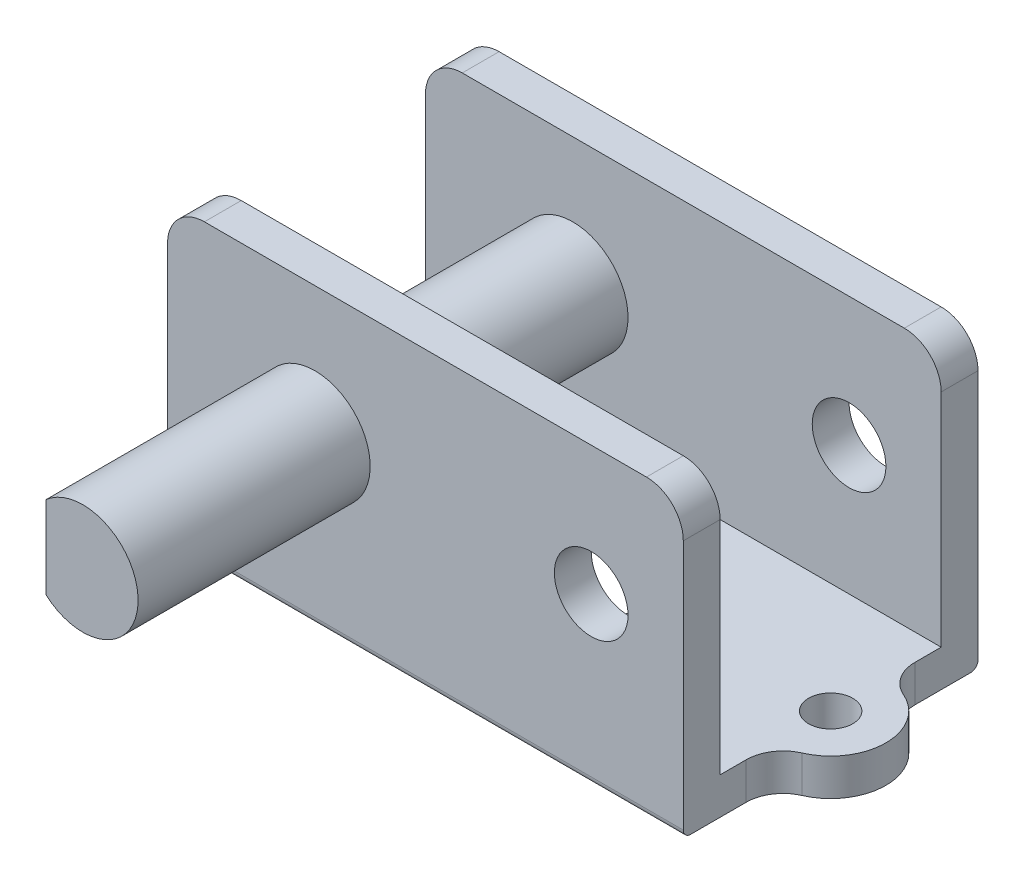
SolidWorks part; units mm, degrees
ref_plane "Спереди" through (0, 0, 0) normal (0, 0, 1) x (1, 0, 0)
ref_plane "Сверху" through (0, 0, 0) normal (0, 1, 0) x (1, 0, 0)
ref_plane "Справа" through (0, 0, 0) normal (1, 0, 0) x (0, 0, -1)
sketch "Sketch1" plane through (0, 0, 0) normal (0, 0, 1) x (1, 0, 0)
  line L0 (0, 0) -> (-7, 0)
  line L1 (-7, 0) -> (-7, 8)
  line L2 (-7, 8) -> (7, 8)
  line L3 (7, 8) -> (7, 0)
  line L4 (7, 0) -> (0, 0)
extrude "Extrude1" add sketch "Sketch1" along normal mid plane 8
sketch "Sketch2" plane through (0, 0, 0) normal (0, 0, 1) x (1, 0, 0)
  line L0 (7, 8) -> (7, 4.5) construction
  line L1 (7, 4.5) -> (4.5, 4.5) construction
  circle A0 centre (4.5, 4.5) radius 1
extrude "Extrude2" cut sketch "Sketch2" against normal through all both and the other way through all
sketch "Sketch3" plane through (0, 0, 0) normal (0, 0, 1) x (1, 0, 0)
  line L0 (-7, 8) -> (-3, 8)
  line L1 (-3, 8) -> (-3, 4.5)
  circle A0 centre (-3, 4.5) radius 1.5
sketch "Sketch4" plane through (0, 0, 0) normal (1, 0, 0) x (0, 0, -1)
  line L0 (0, 0) -> (0, 1)
  line L1 (3, 1) -> (-3, 1)
  line L2 (-3, 1) -> (-3, 9.732)
  line L3 (3, 1) -> (3, 9.732)
  line L4 (-3, 9.732) -> (3, 9.732)
extrude "Extrude3" cut sketch "Sketch4" against normal through all both and the other way through all contours L4 L2 L1 L3
fillet "Fillet1" radius 0.2 2 edges at (0, 0, 4) (0, 0, -4)
fillet "Fillet2" radius 1 4 edges at (7, 8, -3.5) (7, 8, 3.5) (-7, 8, -3.5) (-7, 8, 3.5)
extrude "Extrude4" add sketch "Sketch3" along normal blind 14 and the other way blind 3
sketch "Sketch5" plane through (0, 0, 14) normal (0, 0, 1) x (1, 0, 0)
  line L0 (-1.5, 4.5) -> (-4, 4.5)
  line L1 (-4, 4.5) -> (-4, 6.0607)
  line L2 (-4, 6.0607) -> (-4.9564, 6.0607)
  line L3 (-4.9564, 6.0607) -> (-4.9564, 2.5)
  line L4 (-4.9564, 2.5) -> (-4, 2.5)
  line L5 (-4, 2.5) -> (-4, 4.5)
  circle A0 centre (-3, 4.5) radius 1.5 construction
  circle A1 centre (-3, 4.5) radius 1.5 construction
  circle M1 centre (-3, 4.5) radius 1.5
extrude "Extrude5" cut sketch "Sketch5" against normal blind 9 contours L4 L5 L1 L2 L3 M1 | L5 L1 M1
sketch "Sketch6" plane through (0, 0, 0) normal (0, -1, 0) x (1, 0, 0)
  line L0 (0, 0) -> (-8.5, 0)
  line L2 (0, 0) -> (0, 5.5899)
  circle A1 centre (-7, 0) radius 1.5
  circle A2 centre (0, 0) radius 6
  circle A3 centre (7, 0) radius 1.5
extrude "Extrude6" add sketch "Sketch6" against normal blind 1
sketch "Sketch7" plane through (0, 0, 0) normal (0, -1, 0) x (1, 0, 0)
  circle A0 centre (-7, 0) radius 0.6
  circle A1 centre (7, 0) radius 0.6
extrude "Extrude7" cut sketch "Sketch7" against normal blind 1
fillet "Fillet3" radius 1 4 edges at (7, 0.5, -1.5) (7, 0.5, 1.5) (-7, 0.5, 1.5) (-7, 0.5, -1.5)
sketch "Sketch8" plane through (0, 0, 0) normal (0, -1, 0) x (1, 0, 0)
  circle A0 centre (0, 0) radius 2
extrude "Extrude8" cut sketch "Sketch8" against normal blind 1
sketch "Sketch9" plane through (0, 0, 4) normal (0, 0, 1) x (1, 0, 0)
  circle A0 centre (-3, 4.5) radius 2.1726
extrude "Extrude9" cut sketch "Sketch9" along normal blind 10 from offset 6.3
